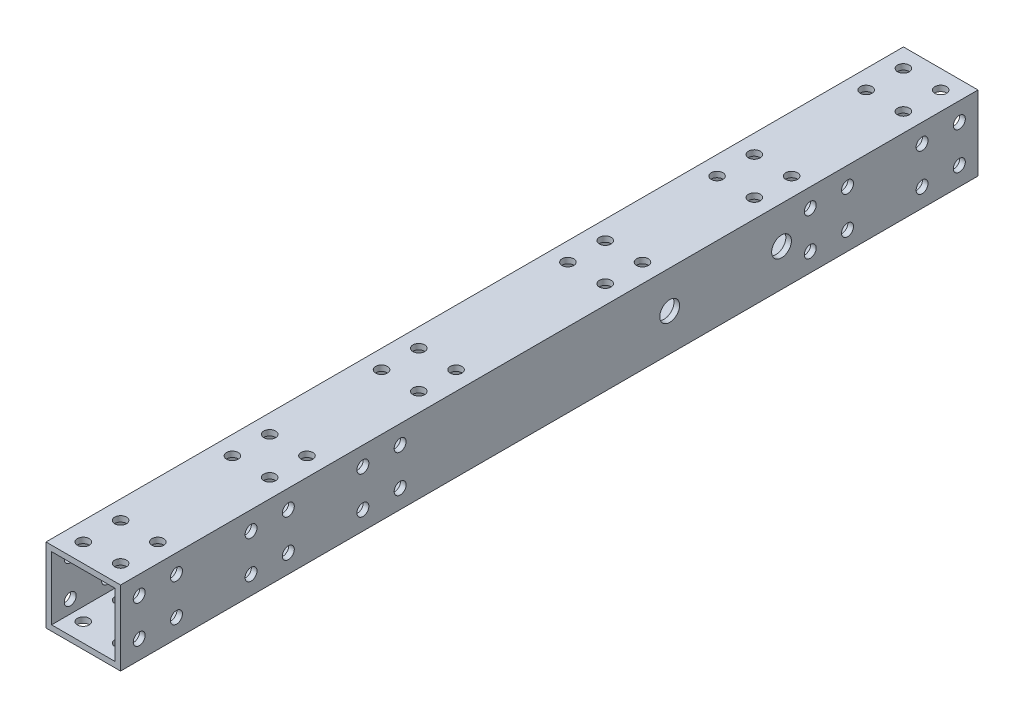
SolidWorks part; units mm, degrees
ref_plane "前视基准面" through (0, 0, 0) normal (0, 0, 1) x (1, 0, 0)
ref_plane "上视基准面" through (0, 0, 0) normal (0, 1, 0) x (1, 0, 0)
ref_plane "右视基准面" through (0, 0, 0) normal (1, 0, 0) x (0, 0, -1)
other "Configuration Table"
sketch "草图1" plane through (0, 0, 0) normal (0, 0, 1) x (1, 0, 0)
  line L1 (0, 0) -> (20, 0)
  line L2 (0, 0) -> (0, -20)
  line L3 (0, -20) -> (20, -20)
  line L4 (20, 0) -> (20, -20)
  dimension "D1" = 20
  dimension "D2" = 20
extrude "拉伸-薄壁1" add sketch "草图1" along normal blind 230 thin
sketch "草图2" plane through (20, 0, 0) normal (1, 0, 0) x (0, 0, -1)
  line L0 (-220, 0) -> (-220, -20) construction
  line L1 (-230, -20) -> (0, -20) construction
  line L2 (-115, 0) -> (-115, -20) construction
  line L3 (-230, 0) -> (0, 0) construction
  line L4 (-220, -10) -> (-230, -10) construction
  line L5 (-230, -20) -> (-230, 0) construction
  line L6 (-10, -10) -> (0, -10) construction
  line L7 (-10, 0) -> (-10, -20) construction
  circle A0 centre (-82.7, -10) radius 2.65
  circle A1 centre (-52.7, -10) radius 2.65
  circle A2 centre (-225, -5) radius 1.6
  circle A3 centre (-225, -15) radius 1.6
  circle A4 centre (-215, -15) radius 1.6
  circle A5 centre (-215, -5) radius 1.6
  circle A6 centre (-195, -5) radius 1.6
  circle A7 centre (-185, -5) radius 1.6
  circle A8 centre (-185, -15) radius 1.6
  circle A9 centre (-195, -15) radius 1.6
  circle A10 centre (-165, -5) radius 1.6
  circle A11 centre (-155, -5) radius 1.6
  circle A12 centre (-155, -15) radius 1.6
  circle A13 centre (-165, -15) radius 1.6
  circle A14 centre (-35, -15) radius 1.6
  circle A15 centre (-45, -15) radius 1.6
  circle A16 centre (-45, -5) radius 1.6
  circle A17 centre (-35, -5) radius 1.6
  circle A18 centre (-15, -5) radius 1.6
  circle A19 centre (-15, -15) radius 1.6
  circle A20 centre (-5, -15) radius 1.6
  circle A21 centre (-5, -5) radius 1.6
  dimension "D2" = 5.3
  dimension "D5" = 3.2
  dimension "D1" = 32.3
  dimension "D3" = 10
  dimension "D4" = 30
  dimension "D6" = 5
  dimension "D7" = 5
  dimension "D8" = 10
  dimension "D9" = 30
extrude "切除-拉伸1" cut sketch "草图2" against normal through all
sketch "草图3" plane through (0, 0, 0) normal (0, 1, 0) x (1, 0, 0)
  line L0 (0, -10) -> (20, -10) construction
  line L1 (0, -230) -> (0, 0) construction
  line L2 (20, -230) -> (20, 0) construction
  line L3 (10, 0) -> (10, -10) construction
  line L4 (20, 0) -> (0, 0) construction
  line L5 (0, -115) -> (20, -115) construction
  line L6 (10, -230) -> (10, -220) construction
  line L7 (0, -220) -> (20, -220) construction
  circle A0 centre (5, -5) radius 1.575
  circle A1 centre (15, -5) radius 1.575
  circle A2 centre (15, -15) radius 1.575
  circle A3 centre (5, -15) radius 1.575
  circle A4 centre (5, -215) radius 1.575
  circle A5 centre (15, -215) radius 1.575
  circle A6 centre (15, -225) radius 1.575
  circle A7 centre (5, -225) radius 1.575
  circle A8 centre (5, -45) radius 1.575
  circle A9 centre (15, -45) radius 1.575
  circle A10 centre (15, -55) radius 1.575
  circle A11 centre (5, -55) radius 1.575
  circle A12 centre (5, -85) radius 1.575
  circle A13 centre (15, -85) radius 1.575
  circle A14 centre (15, -95) radius 1.575
  circle A15 centre (5, -95) radius 1.575
  circle A16 centre (5, -135) radius 1.575
  circle A17 centre (15, -135) radius 1.575
  circle A18 centre (15, -145) radius 1.575
  circle A19 centre (5, -145) radius 1.575
  circle A20 centre (5, -175) radius 1.575
  circle A21 centre (15, -175) radius 1.575
  circle A22 centre (15, -185) radius 1.575
  circle A23 centre (5, -185) radius 1.575
  dimension "D4" = 3.15
  dimension "D1" = 5
  dimension "D2" = 5
  dimension "D3" = 10
  dimension "D5" = 40
extrude "切除-拉伸2" cut sketch "草图3" against normal through all
